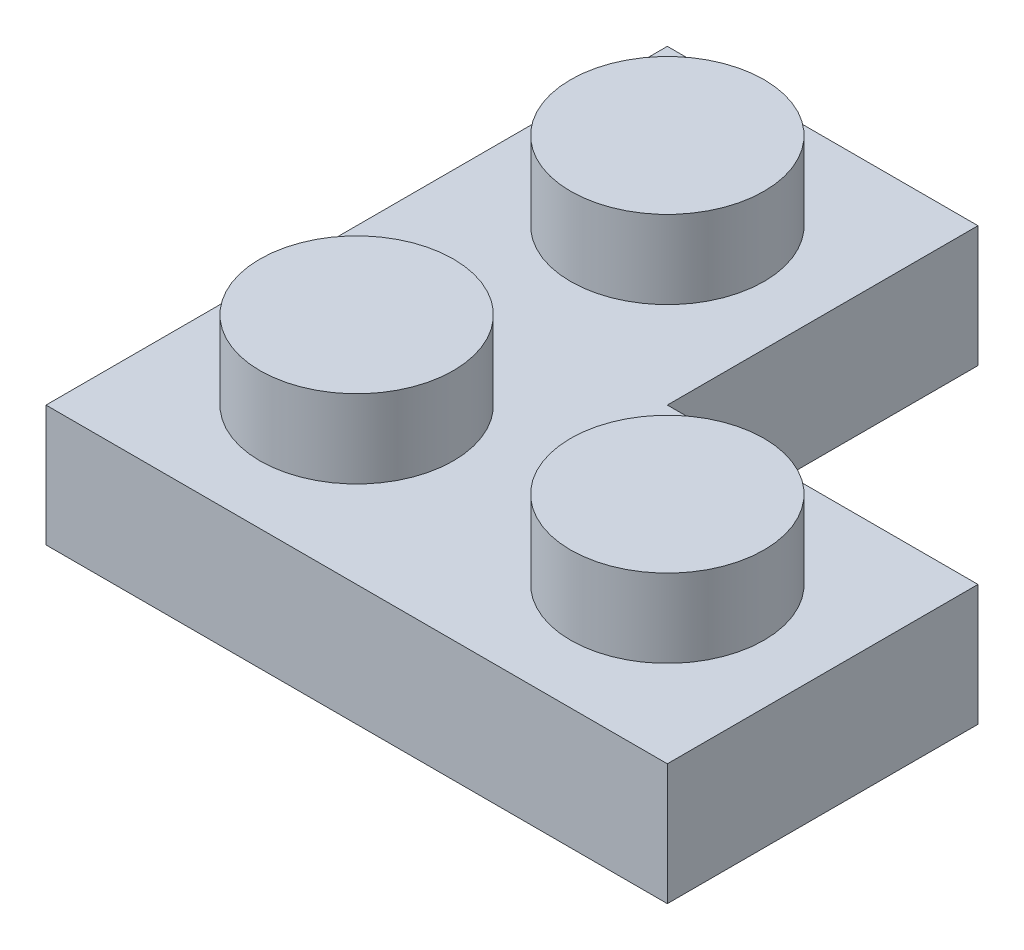
SolidWorks part; units mm, degrees
ref_plane "Front Plane" through (0, 0, 0) normal (0, 0, 1) x (1, 0, 0)
ref_plane "Top Plane" through (0, 0, 0) normal (0, 1, 0) x (1, 0, 0)
ref_plane "Right Plane" through (0, 0, 0) normal (1, 0, 0) x (0, 0, -1)
sketch "Sketch1" plane through (0, 0, 0) normal (0, 1, 0) x (1, 0, 0)
  line L1 (0, 0) -> (7.95, 0)
  line L2 (0, 0) -> (0, -15.9)
  line L3 (0, -15.9) -> (15.9, -15.9)
  line L4 (15.9, -7.95) -> (15.9, -15.9)
  line L7 (15.9, -7.95) -> (7.95, -7.95)
  line L8 (7.95, 0) -> (7.95, -7.95)
  dimension "D1" = 7.95
  dimension "D2" = 15.9
  dimension "D3" = 7.95
  dimension "D4" = 7.95
extrude "Boss-Extrude1" add sketch "Sketch1" along normal blind 3.1
sketch "Sketch2" plane through (0, 3.1, 0) normal (0, 1, 0) x (1, 0, 0)
  line L0 (7.95, -7.95) -> (7.95, 0) construction
  line L1 (0, -15.9) -> (15.9, -15.9) construction
  line L2 (15.9, -15.9) -> (15.9, -7.95) construction
  line L3 (0, 0) -> (0, -15.9) construction
  line L4 (7.95, 0) -> (0, 0) construction
  circle A0 centre (3.975, -3.975) radius 2.475
  circle A1 centre (3.975, -11.925) radius 2.475
  circle A2 centre (11.925, -11.925) radius 2.475
  dimension "D1" = 4.95
  dimension "D2" = 4.95
  dimension "D3" = 4.95
  dimension "D4" = 3.975
  dimension "D5" = 3.975
  dimension "D6" = 3.975
  dimension "D7" = 3.975
  dimension "D8" = 3.975
  dimension "D9" = 3.975
extrude "Boss-Extrude2" add sketch "Sketch2" along normal blind 2
sketch "Sketch3" plane through (0, 0, 0) normal (0, -1, 0) x (1, 0, 0)
  line L0 (1.5, 14.4) -> (1.5, 1.5)
  line L1 (1.5, 1.5) -> (6.45, 1.5)
  line L2 (6.45, 1.5) -> (6.45, 9.45)
  line L3 (6.45, 9.45) -> (14.4, 9.45)
  line L4 (14.4, 9.45) -> (14.4, 14.4)
  line L5 (14.4, 14.4) -> (1.5, 14.4)
  line L6 (0, 15.9) -> (15.9, 15.9) construction
  line L7 (0, 0) -> (0, 15.9) construction
  line L8 (7.95, 0) -> (0, 0) construction
  line L9 (7.95, 7.95) -> (7.95, 0) construction
  line L10 (15.9, 7.95) -> (7.95, 7.95) construction
  line L11 (15.9, 15.9) -> (15.9, 7.95) construction
  dimension "D1" = 1.5
  dimension "D2" = 1.5
  dimension "D3" = 1.5
  dimension "D4" = 1.5
  dimension "D5" = 1.5
  dimension "D6" = 1.5
extrude "Cut-Extrude1" cut sketch "Sketch3" against normal blind 2
